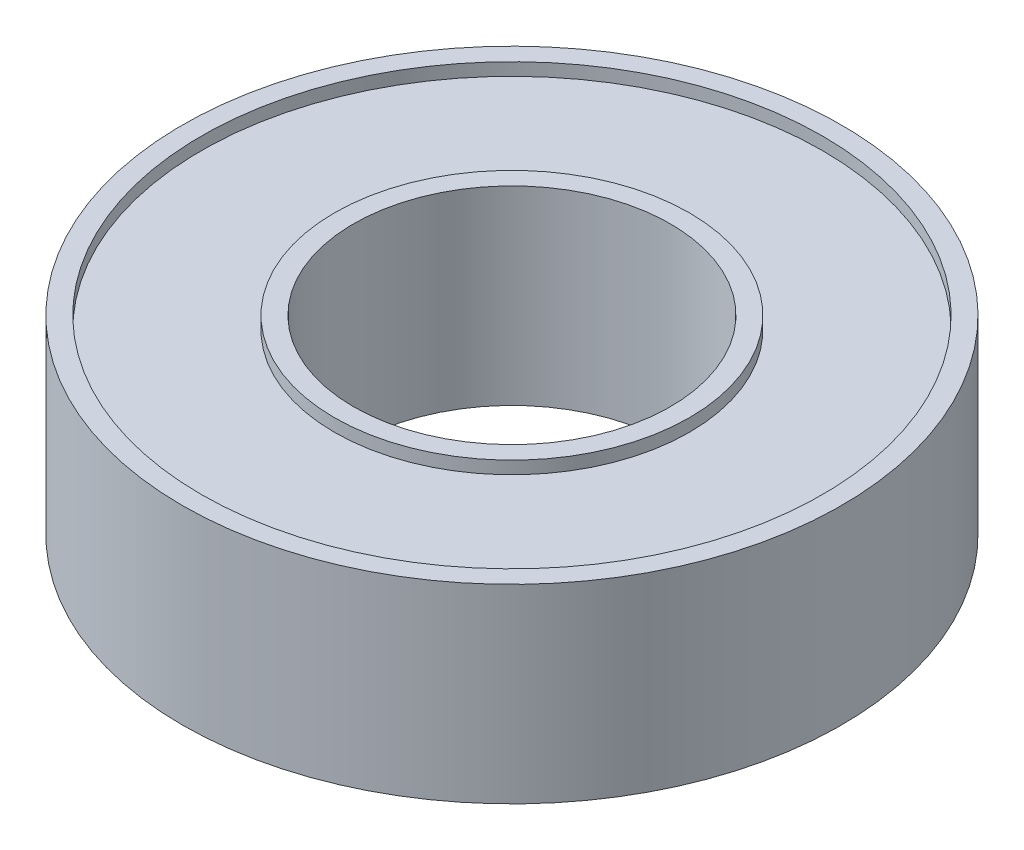
SolidWorks part; units mm, degrees
ref_plane "Alzado" through (0, 0, 0) normal (0, 0, 1) x (1, 0, 0)
ref_plane "Planta" through (0, 0, 0) normal (0, 1, 0) x (1, 0, 0)
ref_plane "Vista lateral" through (0, 0, 0) normal (1, 0, 0) x (0, 0, -1)
sketch "Croquis1" plane through (0, 0, 0) normal (0, 1, 0) x (1, 0, 0)
  circle A0 centre (0, 0) radius 26
  circle A1 centre (0, 0) radius 12.5
  dimension "D1" = 52
  dimension "D2" = 25
extrude "Saliente-Extruir1" add sketch "Croquis1" along normal blind 15 contours A0
sketch "Croquis2" plane through (0, 15, 0) normal (0, 1, 0) x (1, 0, 0)
  circle A0 centre (0, 0) radius 26
  circle A1 centre (0, 0) radius 24.5
  circle A2 centre (0, 0) radius 12.5
  circle A3 centre (0, 0) radius 14
  dimension "D1" = 49
  dimension "D2" = 52
  dimension "D3" = 25
  dimension "D4" = 28
extrude "Cortar-Extruir1" cut sketch "Croquis2" against normal blind 1 contours A1 A3
sketch "Croquis3" plane through (0, 0, 0) normal (0, -1, 0) x (1, 0, 0)
  circle A0 centre (0, 0) radius 26
  circle A1 centre (0, 0) radius 12.5
  circle A2 centre (0, 0) radius 24.5
  circle A3 centre (0, 0) radius 14
  dimension "D1" = 52
  dimension "D2" = 49
  dimension "D3" = 28
  dimension "D4" = 25
extrude "Cortar-Extruir3" cut sketch "Croquis3" against normal blind 1 contours A2 A3
